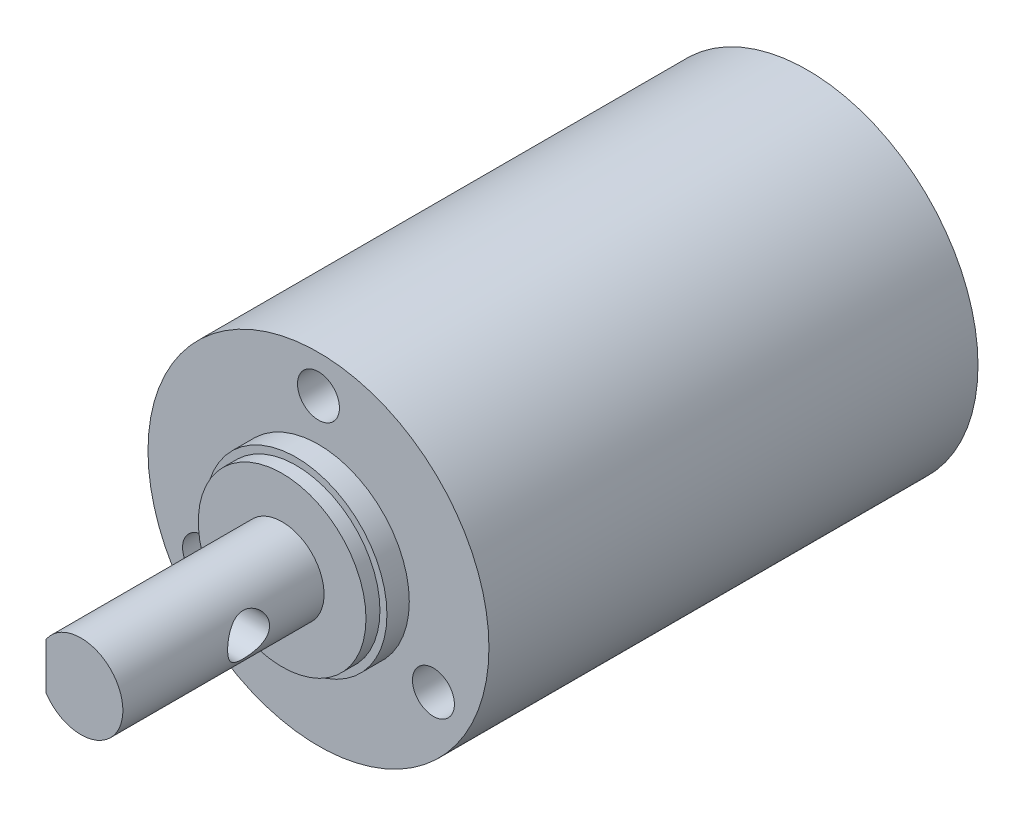
SolidWorks part; units mm, degrees
ref_plane "前视基准面" through (0, 0, 0) normal (0, 0, 1) x (1, 0, 0)
ref_plane "上视基准面" through (0, 0, 0) normal (0, 1, 0) x (1, 0, 0)
ref_plane "右视基准面" through (0, 0, 0) normal (1, 0, 0) x (0, 0, -1)
sketch "草图1" plane through (0, 0, 0) normal (0, 0, 1) x (1, 0, 0)
  circle A0 centre (0, 0) radius 12.2
  dimension "D1" = 24.4
extrude "凸台-拉伸1" add sketch "草图1" along normal blind 35
sketch "草图2" plane through (0, 0, 35) normal (0, 0, 1) x (1, 0, 0)
  circle A0 centre (0, 0) radius 6.5
  dimension "D1" = 13
extrude "凸台-拉伸2" add sketch "草图2" along normal blind 2.6
sketch "草图3" plane through (0, 0, 37.6) normal (0, 0, 1) x (1, 0, 0)
  line L0 (-2.5, 1.6583) -> (-2.5, -1.6583)
  arc A0 (-2.5, -1.6583) -> (-2.5, 1.6583) centre (0, 0) ccw
  dimension "D1" = 6
  dimension "D2" = 2.5
extrude "凸台-拉伸3" add sketch "草图3" along normal blind 14.4
sketch "草图4" plane through (0, 0, 37.6) normal (0, 0, 1) x (1, 0, 0)
  circle A0 centre (0, 0) radius 6
  circle A1 centre (0, 0) radius 6.5
  dimension "D1" = 12
extrude "切除-拉伸2" cut sketch "草图4" against normal blind 1
sketch "草图5" plane through (-2.5, 0, 0) normal (-1, 0, 0) x (0, 0, 1)
  line L0 (52, 1.6583) -> (52, -1.6583) construction
  circle A0 centre (43, 0) radius 1.5
  dimension "D1" = 3
  dimension "D2" = 9
extrude "切除-拉伸3" cut sketch "草图5" against normal through all
sketch "草图6" plane through (0, 0, 35) normal (0, 0, 1) x (1, 0, 0)
  circle A0 centre (0, 0) radius 9.5 construction
  circle A1 centre (0, 9.5) radius 1.5
  circle A2 centre (8.2272, -4.75) radius 1.5
  circle A3 centre (-8.2272, -4.75) radius 1.5
  point P11 (0, 0)
  dimension "D1" = 3
  dimension "D2" = 3
extrude "切除-拉伸5" cut sketch "草图6" against normal blind 4
